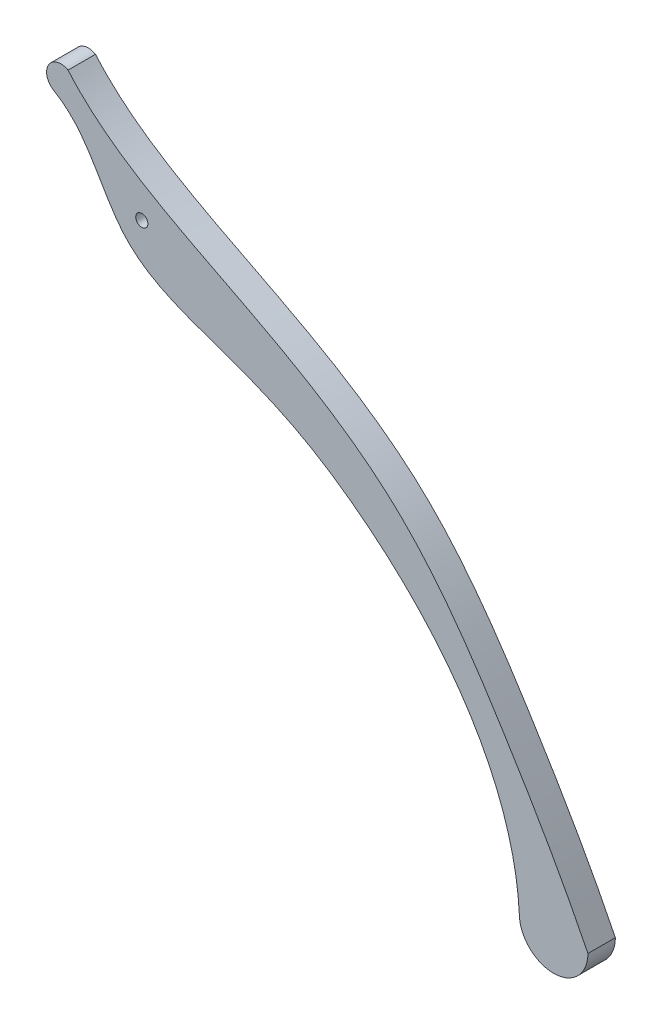
SolidWorks part; units mm, degrees
ref_plane "Plan de face" through (0, 0, 0) normal (0, 0, 1) x (1, 0, 0)
ref_plane "Plan de dessus" through (0, 0, 0) normal (0, 1, 0) x (1, 0, 0)
ref_plane "Plan de droite" through (0, 0, 0) normal (1, 0, 0) x (0, 0, -1)
sketch "Esquisse1" plane through (0, 0, 0) normal (0, 0, 1) x (1, 0, 0)
  line L0 (0, 0) -> (-35.3553, 35.3553) construction
  line L1 (0, 0) -> (180, -180) construction
  line L2 (-38.4803, 29.9427) -> (-32.2303, 40.768) construction
  line L3 (55, 0) -> (-55, 0) construction
  line L4 (-6.25, -10.8253) -> (6.25, 10.8253) construction
  circle A0 centre (0, 0) radius 12.5 construction
  arc A8 (165, -180) -> (195, -180) centre (180, -180) ccw
  circle A11 centre (0, 0) radius 2.65
  arc A12 (-32.2303, 40.768) -> (-38.4803, 29.9427) centre (-35.3553, 35.3553) ccw
  spline S0 degree 3 poles (-32.2303, 40.768) (-21.4871, 28.2858) (6.8174, 8.9856) (57.9076, -15.3354) (116.0007, -50.55) (158.2502, -113.4101) (183.8116, -157.3423) (195, -180) knots 0 0 0 0 0.150864 0.313676 0.525225 0.76792 1 1 1 1
  spline S1 degree 3 poles (-38.4803, 29.9427) (-22.6808, 20.9371) (-13.7884, -16.1248) (31.9147, -30.1515) (67.2534, -43.9694) (125.0616, -82.2157) (162.6075, -132.9509) (165, -180) knots 0 0 0 0 0.170787 0.322786 0.434261 0.547849 1 1 1 1
  point P4 (38.1949, -33.2105)
  point P6 (41.2917, -29.4922)
  point P14 (0, 0)
  point P15 (-35.3553, 35.3553)
  point P18 (39.8438, -32.8706)
  point P22 (0, 0)
  point P26 (0, 0)
  point P29 (71.979, -48.1128)
  point P32 (100.0416, -68.6692)
  point P34 (39.0955, -33.5691)
  point P35 (0, 0)
  point P37 (38.9384, -34.3543)
  point P38 (38.6243, -36.0819)
  point P39 (0, 0)
  point P40 (0, 0)
  point P41 (38.1532, -35.4537)
  point P42 (0, 0)
  point P43 (38.3102, -34.5114)
  point P44 (38.6243, -33.412)
  point P45 (37.0538, -33.412)
  point P46 (36.7397, -32.7838)
  point P47 (35.7974, -32.7838)
  point P48 (35.4833, -32.3127)
  point P49 (35.1692, -31.8415)
  point P50 (71.762, -47.2325)
  point P51 (95.728, -63.8523)
  point P52 (66.5938, -44.9868)
  dimension "D1" = 25
  dimension "D2" = 12.5
  dimension "D3" = 30
  dimension "D9" = 5.3
  dimension "D10" = 25.2987
  dimension "D4" = 50
  dimension "D5" = 254.5584
  dimension "D6" = 45
  dimension "D7" = 180
  dimension "D8" = 60
extrude "Boss.-Extru.1" add sketch "Esquisse1" along normal blind 12
